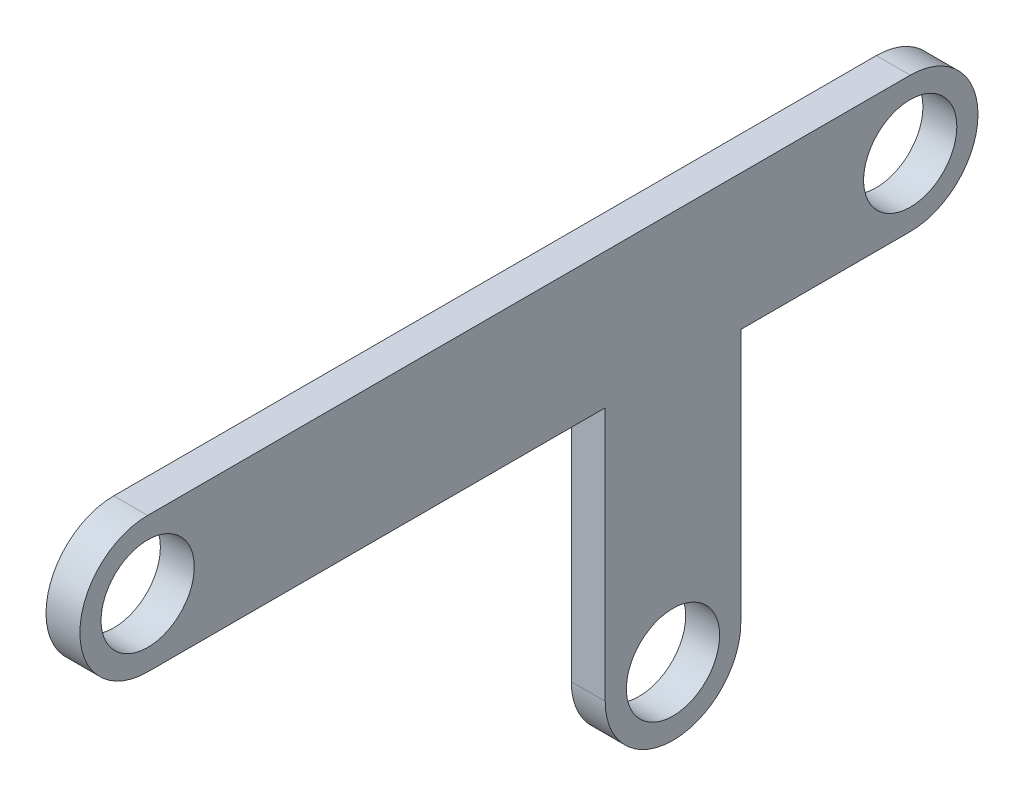
SolidWorks part; units mm, degrees
ref_plane "Front Plane" through (0, 0, 0) normal (0, 0, 1) x (1, 0, 0)
ref_plane "Top Plane" through (0, 0, 0) normal (0, 1, 0) x (1, 0, 0)
ref_plane "Right Plane" through (0, 0, 0) normal (1, 0, 0) x (0, 0, -1)
sketch "Sketch1" plane through (0, 0, 0) normal (1, 0, 0) x (0, 0, -1)
  line L0 (0, 4) -> (40, 4) construction
  line L1 (4, 0) -> (31, 0)
  line L3 (4, 8) -> (49, 8)
  line L6 (39, 0) -> (39, -15)
  line L8 (31, 0) -> (31, -15)
  line L9 (35, -19) -> (35, 8) construction
  line L10 (39, 0) -> (49, 0)
  circle A0 centre (4, 4) radius 2.75
  circle A1 centre (35, -15) radius 2.75
  circle A2 centre (49, 4) radius 2.75
  arc A3 (49, 0) -> (49, 8) centre (49, 4) ccw
  arc A4 (4, 8) -> (4, 0) centre (4, 4) ccw
  arc A5 (31, -15) -> (39, -15) centre (35, -15) ccw
  dimension "D5" = 5.5
  dimension "D6" = 5.5
  dimension "5.50mm" = 5.5
  dimension "D1" = 45
  dimension "D2" = 10
  dimension "D3" = 15
  dimension "D4" = 8
extrude "Boss-Extrude1" add sketch "Sketch1" along normal blind 2
